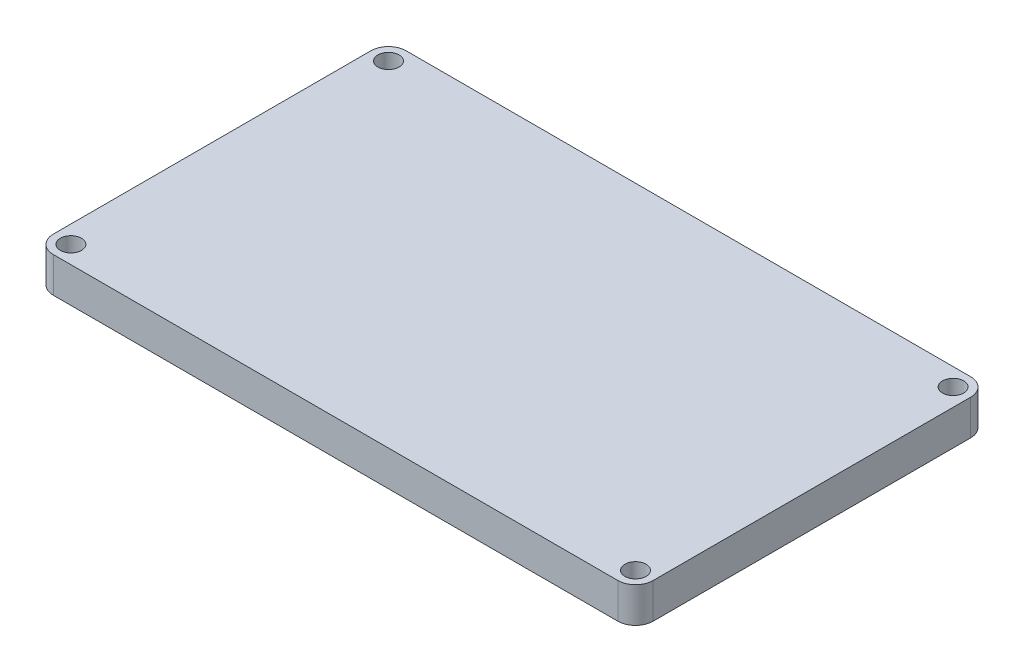
SolidWorks part; units mm, degrees
material "ABS PC"
ref_plane "Front Plane" through (0, 0, 0) normal (0, 0, 1) x (1, 0, 0)
ref_plane "Top Plane" through (0, 0, 0) normal (0, 1, 0) x (1, 0, 0)
ref_plane "Right Plane" through (0, 0, 0) normal (1, 0, 0) x (0, 0, -1)
sketch "Sketch1" plane through (0, 0, 0) normal (0, 1, 0) x (1, 0, 0)
  line L0 (-70.6896, 40.7853) -> (-70.6896, -59.2147)
  line L1 (-70.6896, 40.7853) -> (99.3104, 40.7853)
  line L2 (-70.6896, -59.2147) -> (99.3104, -59.2147)
  line L3 (99.3104, 40.7853) -> (99.3104, -59.2147)
  line L4 (-70.6896, -59.2147) -> (-70.6896, -54.2147)
  line L5 (-70.6896, -59.2147) -> (-65.6896, -59.2147)
  line L6 (-70.6896, -54.2147) -> (-65.6896, -54.2147)
  line L7 (-65.6896, -59.2147) -> (-65.6896, -54.2147)
  line L8 (-70.6896, -9.2147) -> (99.3104, -9.2147) construction
  line L9 (14.3104, 40.7853) -> (14.3104, -59.2147) construction
  circle A0 centre (-65.6896, -54.2147) radius 3
  circle A1 centre (-65.6896, 35.7853) radius 3
  circle A2 centre (94.3104, -54.2147) radius 3
  circle A3 centre (94.3104, 35.7853) radius 3
  dimension "D5" = 6
  dimension "D1" = 170
  dimension "D2" = 100
  dimension "D3" = 5
  dimension "D4" = 5
extrude "Boss-Extrude2" add sketch "Sketch1" along normal blind 10 contours A0 L7 L2 L3 L1 L0 L6 A3 A1 A2 | A0 L6 L0 L2 L7
fillet "Fillet1" radius 5 1 edges at (-70.6896, 5, 59.2147)
fillet "Fillet2" radius 5 3 edges at (99.3104, 5, 59.2147) (99.3104, 5, -40.7853) (-70.6896, 5, -40.7853)
